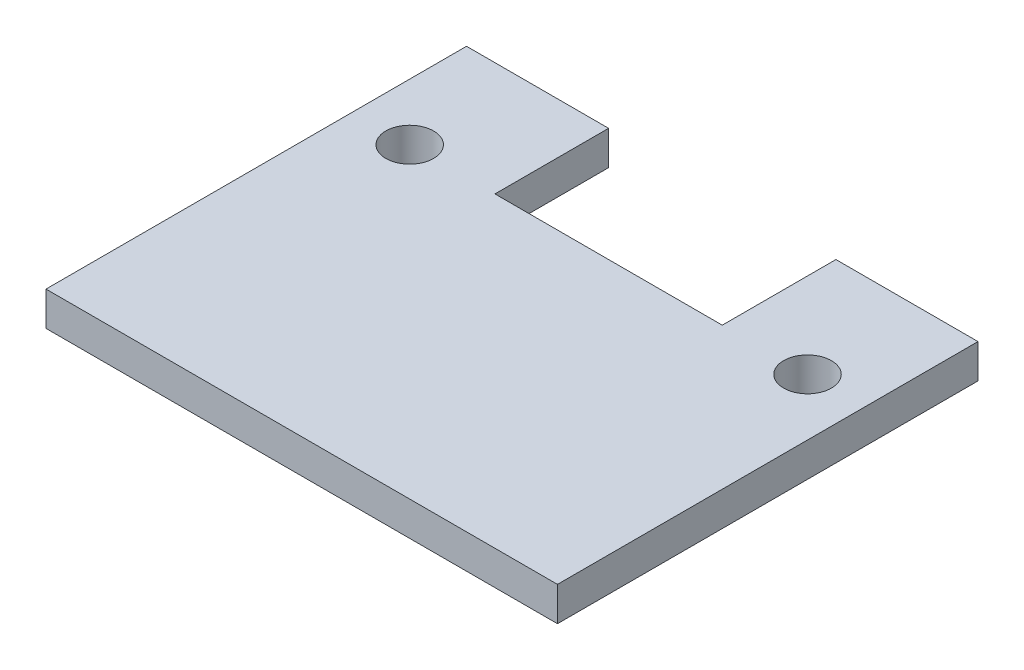
SolidWorks part; units mm, degrees
ref_plane "Ebene vorne" through (0, 0, 0) normal (0, 0, 1) x (1, 0, 0)
ref_plane "Ebene oben" through (0, 0, 0) normal (0, 1, 0) x (1, 0, 0)
ref_plane "Ebene rechts" through (0, 0, 0) normal (1, 0, 0) x (0, 0, -1)
sketch "Skizze2" plane through (0, 0, 0) normal (0, 1, 0) x (1, 0, 0)
  line L5 (-22.5, -18.5) -> (22.5, -18.5)
  line L6 (-22.5, -18.5) -> (-22.5, 18.5)
  line L7 (-22.5, 18.5) -> (22.5, 18.5)
  line L8 (22.5, -18.5) -> (22.5, 18.5)
  line L9 (-22.5, -18.5) -> (22.5, 18.5) construction
  line L10 (-22.5, 18.5) -> (22.5, -18.5) construction
  line L11 (-10, 18.5) -> (10, 18.5)
  line L12 (-10, 18.5) -> (-10, 8.5)
  line L13 (-10, 8.5) -> (10, 8.5)
  line L14 (10, 18.5) -> (10, 8.5)
  circle A0 centre (-17.5, 8.5) radius 2.1
  circle A1 centre (17.5, 8.5) radius 2.1
  point P0 (0, 0)
  dimension "D5" = 4.2
  dimension "D1" = 45
  dimension "D2" = 37
  dimension "D3" = 35
  dimension "D4" = 5
  dimension "D6" = 20
  dimension "D7" = 10
  dimension "D8" = 12.5
  dimension "D9" = 10
  dimension "D10" = 10
extrude "Aufsatz-Linear austragen1" add sketch "Skizze2" along normal blind 3 contours L7 L14 L13 L12 L6 L5 L8 A1 A0
sketch "Skizze3" plane through (0, 3, 0) normal (0, 1, 0) x (1, 0, 0)
  line L0 (22.5, -18.5) -> (22.5, 18.5) construction
  line L1 (-22.5, -18.5) -> (22.5, -18.5)
  line L3 (-22.5, -14.5) -> (22.5, -14.5)
  dimension "D1" = 4
